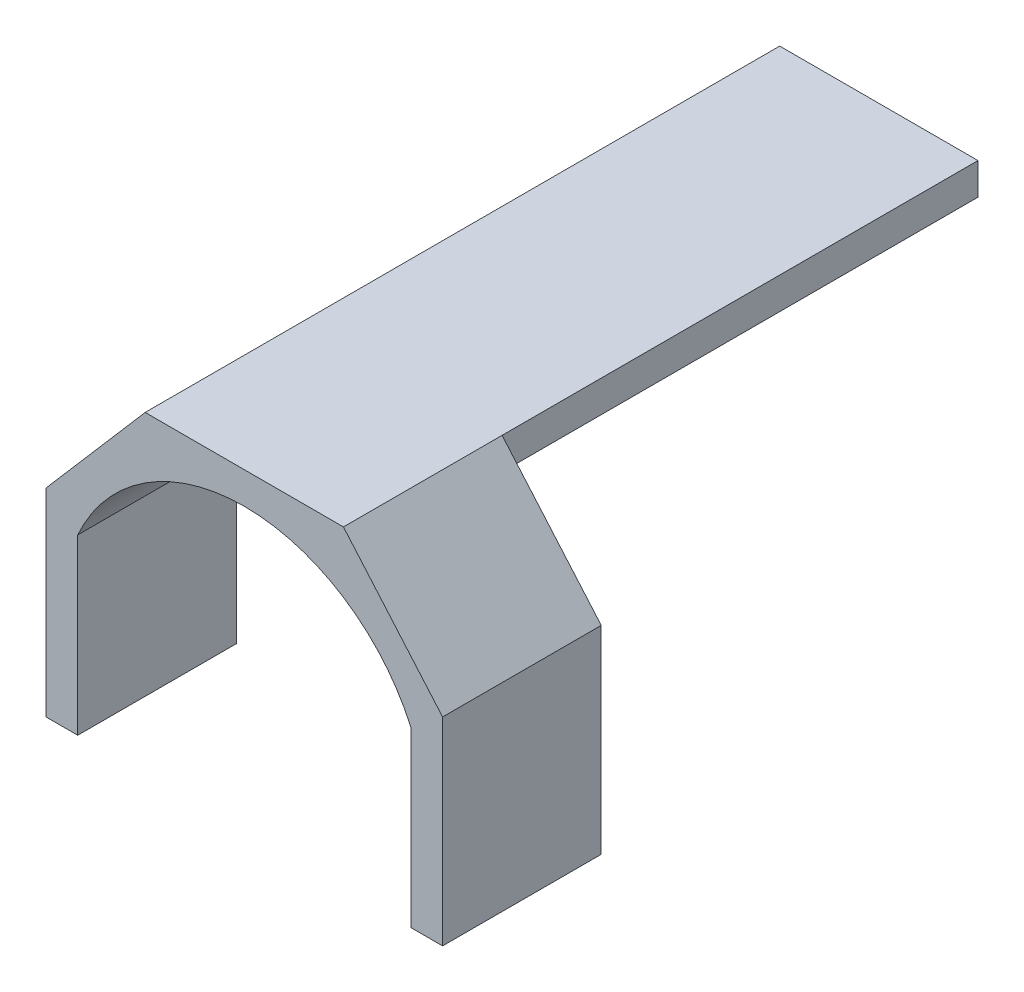
SolidWorks part; units mm, degrees
ref_plane "前视基准面" through (0, 0, 0) normal (0, 0, 1) x (1, 0, 0)
ref_plane "上视基准面" through (0, 0, 0) normal (0, 1, 0) x (1, 0, 0)
ref_plane "右视基准面" through (0, 0, 0) normal (1, 0, 0) x (0, 0, -1)
sketch "草图1" plane through (0, 0, 0) normal (0, 0, 1) x (1, 0, 0)
  line L0 (-39.8017, 0) -> (0, 0) construction
  line L1 (0, 0) -> (0, 40.2975) construction
  line L3 (-25, 4) -> (25, 4)
  line L4 (-25, 4) -> (-25, -4)
  line L5 (-25, -4) -> (25, -4)
  line L6 (25, 4) -> (25, -4)
  dimension "D1" = 50
  dimension "D2" = 25
  dimension "D3" = 8
  dimension "D4" = 4
sketch "草图2" plane through (0, 0, 0) normal (1, 0, 0) x (0, 0, -1)
  line L0 (0, 55.2983) -> (-160, 55.2983)
  line L1 (0, 4) -> (0, -4) construction
  line L2 (0, 4) -> (0, -4) construction
sweep "扫描1" add profiles "草图1" path "草图2"
sketch "草图4" plane through (0, 0, 160) normal (0, 0, 1) x (1, 0, 0)
  line L0 (0, -4) -> (0, -65.5134) construction
  line L4 (-25, -4) -> (25, -4) construction
  line L5 (-50.7277, -50) -> (-46, -50) construction
  line L6 (-50, -25) -> (-25, 4)
  line L8 (-50, -25) -> (-50, -75)
  line L9 (-50, -75) -> (-42, -75)
  line L10 (-42, -31.2383) -> (-42, -75)
  line L12 (42, -31.2383) -> (42, -75)
  line L13 (42, -75) -> (50, -75)
  line L14 (50, -25) -> (50, -75)
  line L15 (-25, 4) -> (25, 4)
  line L16 (25, 4) -> (50, -25)
  line L17 (-42, -50) -> (42, -50) construction
  arc A3 (42, -31.2383) -> (-42, -31.2383) centre (0, -50) ccw
  dimension "D2" = 50
  dimension "D1" = 8
  dimension "D3" = 25
  dimension "D4" = 50
  dimension "D5" = 50
  dimension "D6" = 25
  dimension "D7" = 50
  dimension "D8" = 8
extrude "凸台-拉伸1" add sketch "草图4" against normal blind 40
